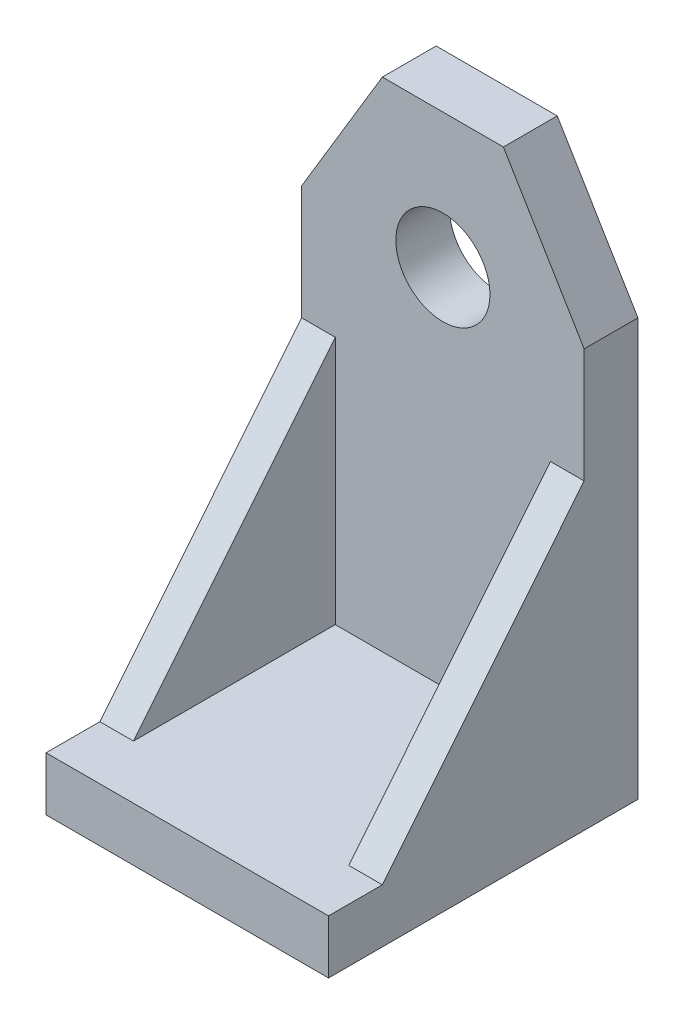
SolidWorks part; units mm, degrees
ref_plane "Front Plane" through (0, 0, 0) normal (0, 0, 1) x (1, 0, 0)
ref_plane "Top Plane" through (0, 0, 0) normal (0, 1, 0) x (1, 0, 0)
ref_plane "Right Plane" through (0, 0, 0) normal (1, 0, 0) x (0, 0, -1)
sketch "Sketch2" plane through (0, 0, 0) normal (0, 0, 1) x (1, 0, 0)
  line L1 (0, 0) -> (42, 0)
  line L2 (0, 0) -> (0, 8)
  line L3 (0, 8) -> (42, 8)
  line L4 (42, 0) -> (42, 8)
  dimension "D1" = 42
  dimension "D2" = 8
extrude "Boss-Extrude1" add sketch "Sketch2" along normal mid plane 46
sketch "Sketch3" plane through (0, 8, 0) normal (0, 1, 0) x (1, 0, 0)
  line L0 (0, 23) -> (42, 23)
  line L1 (42, 23) -> (0, 23) construction
  line L2 (42, 23) -> (42, 15)
  line L3 (42, -23) -> (42, 23) construction
  line L4 (42, 15) -> (0, 15)
  line L5 (0, -23) -> (0, 23) construction
  line L6 (0, 15) -> (0, 23)
  dimension "D1" = 8
extrude "Boss-Extrude2" add sketch "Sketch3" along normal blind 74
sketch "Sketch4" plane through (0, 0, -15) normal (0, 0, 1) x (1, 0, 0)
  line L0 (0, 82) -> (12, 82)
  line L1 (0, 82) -> (42, 82) construction
  line L2 (12, 82) -> (0, 62)
  line L3 (0, 82) -> (0, 8) construction
  line L4 (0, 62) -> (0, 82)
  line L5 (30, 82) -> (42, 82)
  line L6 (42, 82) -> (42, 62)
  line L7 (42, 82) -> (42, 8) construction
  line L8 (42, 62) -> (30, 82)
  point P11 (0, 0)
  dimension "D1" = 12
  dimension "D2" = 12
  dimension "D3" = 62
extrude "Cut-Extrude1" cut sketch "Sketch4" against normal through all
sketch "Sketch6" plane through (0, 0, 0) normal (1, 0, 0) x (0, 0, -1)
  line L0 (15, 45) -> (-15, 8)
  line L1 (15, 62) -> (15, 8) construction
  line L2 (-23, 8) -> (15, 8) construction
  line L3 (-15, 8) -> (15, 8)
  line L4 (15, 8) -> (15, 45)
  dimension "D1" = 17
  dimension "D2" = 8
extrude "Boss-Extrude3" add sketch "Sketch6" along normal blind 5
ref_plane "Plane2" through (42, 0, 0) normal (1, 0, 0) x (0, 0, -1)
sketch "Sketch10" plane through (42, 0, 0) normal (1, 0, 0) x (0, 0, -1)
  line L0 (15, 45) -> (-15, 8)
  line L1 (-15, 8) -> (15, 8)
  line L2 (15, 8) -> (15, 45)
extrude "Boss-Extrude5" add sketch "Sketch10" against normal blind 5
sketch "Sketch11" plane through (0, 0, -15) normal (0, 0, 1) x (1, 0, 0)
  line L0 (12, 82) -> (30, 82) construction
  circle A0 centre (21, 62) radius 7
  point P4 (21, 82)
  dimension "D1" = 14
  dimension "D2" = 20
extrude "Cut-Extrude2" cut sketch "Sketch11" against normal through all
